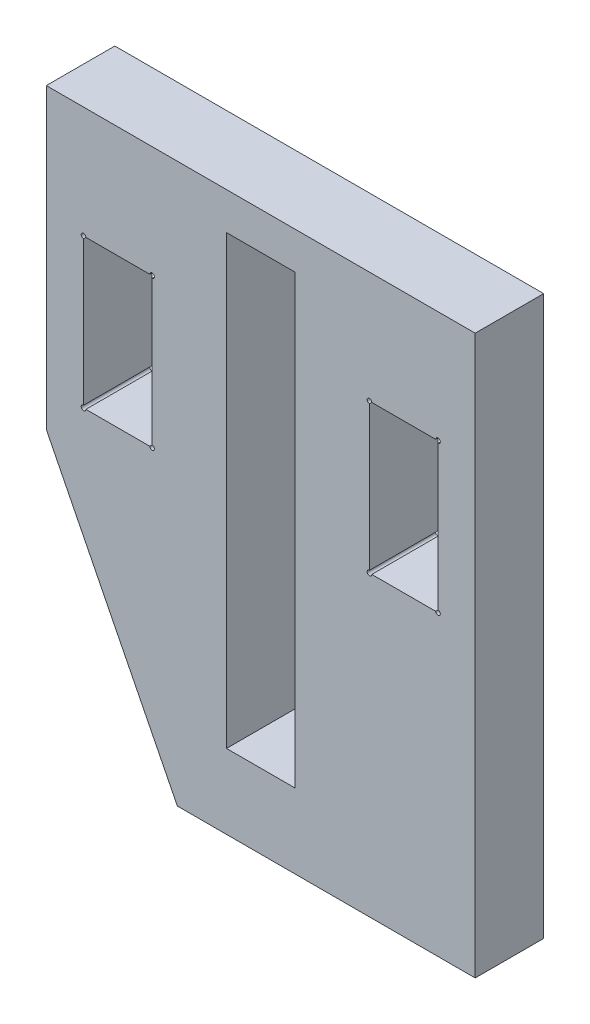
SolidWorks part; units mm, degrees
ref_plane "Front Plane" through (0, 0, 0) normal (0, 0, 1) x (1, 0, 0)
ref_plane "Top Plane" through (0, 0, 0) normal (0, 1, 0) x (1, 0, 0)
ref_plane "Right Plane" through (0, 0, 0) normal (1, 0, 0) x (0, 0, -1)
sketch "Sketch1" plane through (0, 0, 0) normal (0, 0, 1) x (1, 0, 0)
  line L0 (-5.842, 6.35) -> (0, 6.35) construction
  line L1 (0, 0) -> (-5.842, 0)
  line L2 (0, 0) -> (0, 12.7)
  line L3 (0, 12.7) -> (-5.842, 12.7)
  line L4 (-5.842, 0) -> (-5.842, 12.7)
  line L5 (-2.921, 12.7) -> (-2.921, 0) construction
  line L6 (2.159, -25.4) -> (-9.017, -3.175)
  line L7 (-9.017, 22.225) -> (6.35, 22.225)
  line L8 (-9.017, 22.225) -> (-9.017, -3.175)
  line L9 (2.159, -25.4) -> (27.559, -25.4)
  line L10 (27.559, 22.225) -> (27.559, -25.4)
  line L12 (12.192, 0) -> (12.192, -12.7)
  line L13 (18.542, 12.7) -> (24.384, 12.7)
  line L14 (6.35, 0) -> (6.35, -12.7)
  line L15 (12.192, 22.225) -> (27.559, 22.225)
  line L16 (6.35, 19.05) -> (6.35, 0)
  line L17 (12.192, 0) -> (12.192, 19.05)
  line L18 (6.35, 22.225) -> (12.192, 22.225)
  line L19 (18.542, 12.7) -> (18.542, 0)
  line L20 (6.35, 19.05) -> (12.192, 19.05)
  line L21 (6.35, -12.7) -> (6.35, -19.05)
  line L22 (6.35, -19.05) -> (12.192, -19.05)
  line L23 (12.192, -12.7) -> (12.192, -19.05)
  line L24 (18.542, 0) -> (24.384, 0)
  line L25 (24.384, 12.7) -> (24.384, 0)
  dimension "D1" = 5.842
  dimension "D2" = 12.7
  dimension "D3" = 5.842
  dimension "D4" = 12.7
  dimension "D5" = 6.35
  dimension "D6" = 6.35
  dimension "D7" = 12.7
  dimension "D8" = 3.175
  dimension "D9" = 47.625
  dimension "D10" = 6.35
  dimension "D11" = 25.4
  dimension "D12" = 25.4
  dimension "D13" = 3.175
  dimension "D14" = 6.35
  dimension "D15" = 5.842
  dimension "D16" = 3.175
  dimension "D17" = 36.576
extrude "Boss-Extrude1" add sketch "Sketch1" along normal blind 5.842
sketch "Sketch2" plane through (0, 0, 5.842) normal (0, 0, 1) x (1, 0, 0)
  line L0 (-2.921, 12.7) -> (-2.921, 0) construction
  line L1 (0, 12.7) -> (-5.842, 12.7) construction
  line L2 (-5.842, 0) -> (0, 0) construction
  line L3 (0, 6.35) -> (-5.842, 6.35) construction
  line L4 (0, 0) -> (0, 12.7) construction
  line L5 (-5.842, 12.7) -> (-5.842, 0) construction
  line L6 (6.35, 0) -> (12.192, 0) construction
  line L7 (6.35, 19.05) -> (6.35, -19.05) construction
  line L8 (12.192, -19.05) -> (12.192, 19.05) construction
  line L9 (9.271, 19.05) -> (9.271, -19.05) construction
  line L12 (12.192, 19.05) -> (6.35, 19.05) construction
  line L13 (6.35, -19.05) -> (12.192, -19.05) construction
  line L14 (18.542, 6.35) -> (24.384, 6.35) construction
  line L15 (21.463, 12.7) -> (21.463, 0) construction
  circle A0 centre (-5.842, 12.7) radius 0.1984
  circle A1 centre (0, 12.7) radius 0.1984
  circle A2 centre (0, 0) radius 0.1984
  circle A3 centre (-5.842, 0) radius 0.1984
  circle A4 centre (24.384, 0) radius 0.1984
  circle A5 centre (18.542, 0) radius 0.1984
  circle A6 centre (18.542, 12.7) radius 0.1984
  circle A7 centre (24.384, 12.7) radius 0.1984
extrude "Cut-Extrude1" cut sketch "Sketch2" against normal blind 5.842
